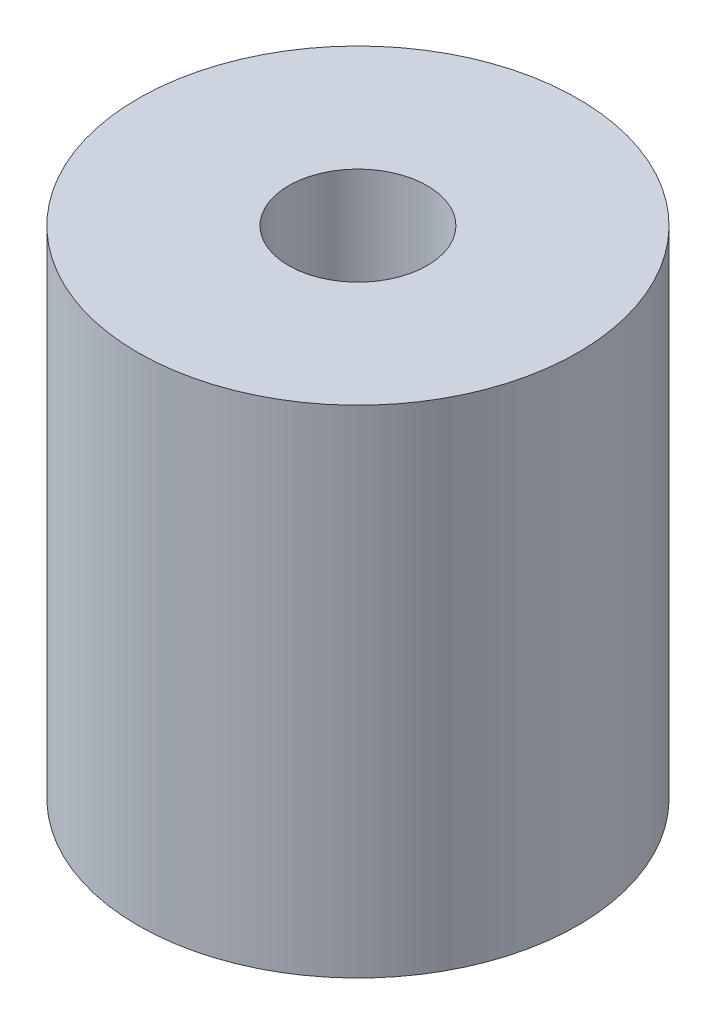
SolidWorks part; units mm, degrees
ref_plane "Front Plane" through (0, 0, 0) normal (0, 0, 1) x (1, 0, 0)
ref_plane "Top Plane" through (0, 0, 0) normal (0, 1, 0) x (1, 0, 0)
ref_plane "Right Plane" through (0, 0, 0) normal (1, 0, 0) x (0, 0, -1)
sketch "Sketch1" plane through (0, 0, 0) normal (0, 1, 0) x (1, 0, 0)
  circle A0 centre (0, 0) radius 5
  circle A1 centre (0, 0) radius 1.575
  dimension "D1" = 10
  dimension "D2" = 3.15
extrude "Boss-Extrude1" add sketch "Sketch1" along normal blind 11.275
sketch "Sketch2" plane through (0, 11.275, 0) normal (0, 1, 0) x (1, 0, 0)
  circle A0 centre (0, 0) radius 1.925
  dimension "D1" = 3.85
extrude "Cut-Extrude1" [suppressed] cut sketch "Sketch2" against normal blind 4
equation "\"D1@Boss-Extrude1\"=\"sheetThickness\"*2+0.5*\"ballBearDiam\""
equation "\"largeBearOD\"= 21mm"
equation "\"largeBearID\" = 15mm"
equation "\"largeBearOTight\"= 0.34375mm'calibrate - hold onto gears"
equation "\"largeBearITight\"= 0mm'calibrate - hold onto eccentric nut"
equation "\"largeBearFlangeDiam\" = 22.5mm"
equation "\"largeBearFlangeWidth\" = 0.8mm"
equation "\"smallBearOD\"= 14.8mm"
equation "\"smallBearOTight\"= 0mm'calibrate - hold onto bottom of gearbox"
equation "\"smallBearOLoose\"= 0mm'calibrate - able to take off topHat"
equation "\"smallBearID\" = 10mm"
equation "\"smallBearITight\" = 0mm'hold onto "
equation "\"pinCircleDiam\"= 75mm"
equation "\"pinDiam\"= 6mm"
equation "\"sheetThickness\"= 0.1875in"
equation "\"ballBearDiam\"= 3.5mm"
equation "\"thrustBearingThickness\"= 5mm'measure this irl and change"
equation "\"thrustBearingID\"= 0mm'measure this irl and change"
equation "\"thrustBearingOD\"= 0mm'measure this irl and change"
equation "\"eccentricity\" = 1mm"
